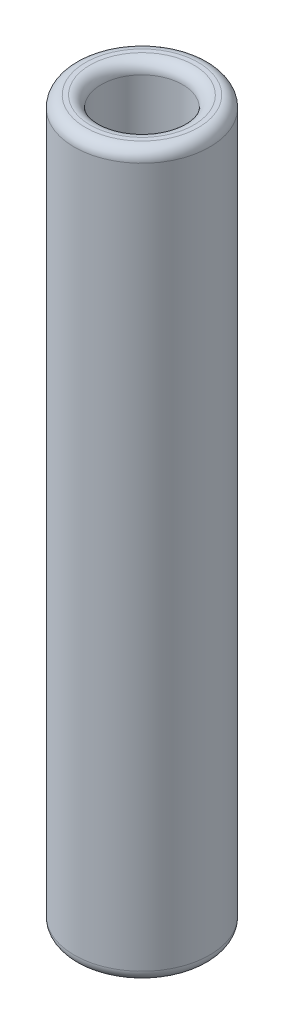
SolidWorks part; units mm, degrees
ref_plane "Front Plane" through (0, 0, 0) normal (0, 0, 1) x (1, 0, 0)
ref_plane "Top Plane" through (0, 0, 0) normal (0, 1, 0) x (1, 0, 0)
ref_plane "Right Plane" through (0, 0, 0) normal (1, 0, 0) x (0, 0, -1)
sketch "Sketch1" plane through (0, 0, 0) normal (0, 1, 0) x (1, 0, 0)
  circle A0 centre (0, 0) radius 2.286
  circle A1 centre (0, 0) radius 3.81
  dimension "D1" = 4.572
  dimension "D2" = 7.62
extrude "Boss-Extrude1" add sketch "Sketch1" along normal blind 40.64
fillet "Fillet1" radius 0.635 4 edges at (0, 0, 2.286) (0, 0, 3.81) (0, 40.64, 2.286) (0, 40.64, 3.81)
